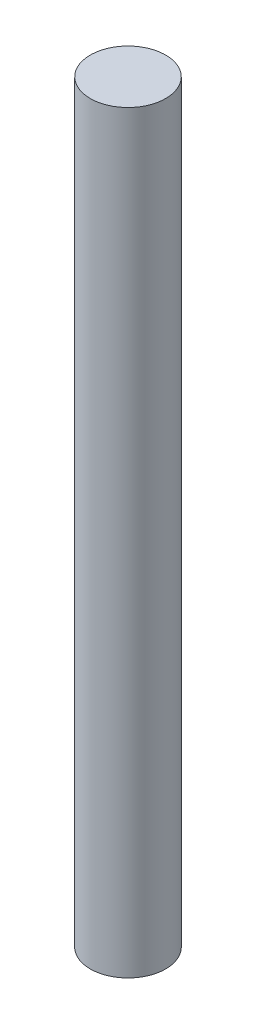
SolidWorks part; units mm, degrees
ref_plane "Front Plane" through (0, 0, 0) normal (0, 0, 1) x (1, 0, 0)
ref_plane "Top Plane" through (0, 0, 0) normal (0, 1, 0) x (1, 0, 0)
ref_plane "Right Plane" through (0, 0, 0) normal (1, 0, 0) x (0, 0, -1)
sketch "Sketch1" plane through (0, 0, 0) normal (0, 1, 0) x (1, 0, 0)
  circle A0 centre (0, 0) radius 10
extrude "Extrude1" add sketch "Sketch1" along normal blind 200
sketch "Sketch2" plane through (0, 0, 0) normal (0, -1, 0) x (1, 0, 0)
  point P0 (0, 0)
sketch "Sketch3" plane through (0, 200, 0) normal (0, 1, 0) x (-1, 0, 0)
  point P0 (0, 0)
